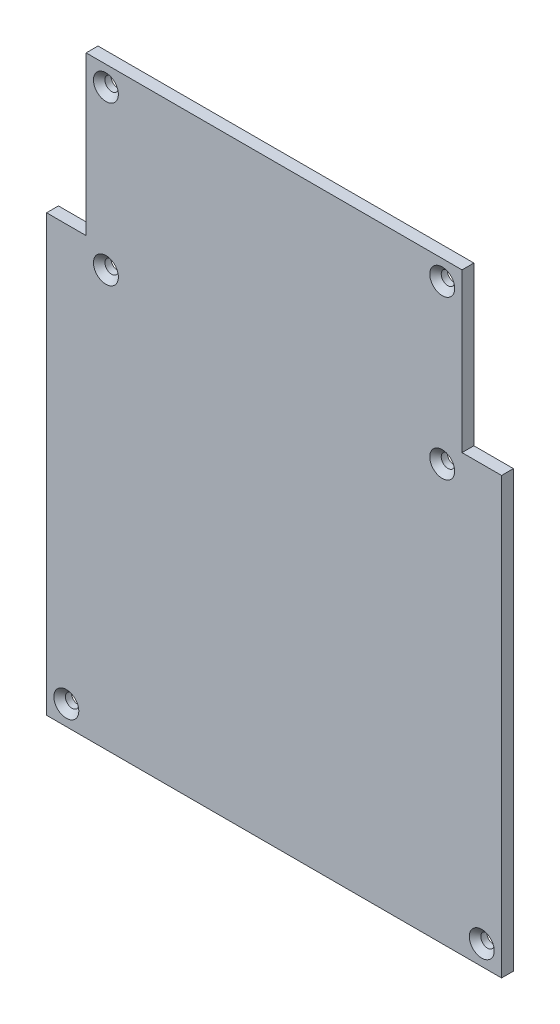
SolidWorks part; units mm, degrees
ref_plane "前基準面" through (0, 0, 0) normal (0, 0, 1) x (1, 0, 0)
ref_plane "上基準面" through (0, 0, 0) normal (0, 1, 0) x (1, 0, 0)
ref_plane "右基準面" through (0, 0, 0) normal (1, 0, 0) x (0, 0, -1)
sketch "草圖1" plane through (0, 0, 0) normal (0, 0, 1) x (1, 0, 0)
  line L0 (0, 75) -> (0, 0) construction
  line L1 (-57.5, -55) -> (57.5, -55)
  line L2 (-57.5, -55) -> (-57.5, 55)
  line L3 (-57.5, 55) -> (-47.5, 55)
  line L4 (57.5, -55) -> (57.5, 55)
  line L5 (-57.5, -55) -> (57.5, 55) construction
  line L6 (-57.5, 55) -> (57.5, -55) construction
  line L7 (-47.5, 95) -> (47.5, 95)
  line L8 (-47.5, 95) -> (-47.5, 55)
  line L10 (47.5, 95) -> (47.5, 55)
  line L11 (-47.5, 95) -> (47.5, 55) construction
  line L12 (-47.5, 55) -> (47.5, 95) construction
  line L13 (47.5, 55) -> (57.5, 55)
  point P0 (0, 0)
  point P6 (0, 75)
  dimension "D1" = 115
  dimension "D2" = 150
  dimension "D3" = 40
  dimension "D4" = 95
extrude "填料-伸長1" add sketch "草圖1" along normal blind 3
hole_wizard "M3 錐坑平頭螺釘的錐孔1" positions "草圖2" profile "草圖3" countersink size "M3" standard "ISO"
sketch "草圖2" plane through (0, 0, 3) normal (0, 0, 1) x (1, 0, 0)
  line L0 (-57.5, 55) -> (-57.5, -55) construction
  line L1 (57.5, -55) -> (57.5, 55) construction
  line L2 (-57.5, -55) -> (57.5, -55) construction
  line L3 (47.5, 95) -> (-47.5, 95) construction
  line L4 (-47.5, 95) -> (-47.5, 55) construction
  line L5 (47.5, 55) -> (47.5, 95) construction
  line L6 (57.5, 55) -> (47.5, 55) construction
  point P0 (-52.5, -50)
  point P2 (-42.5, 90)
  point P4 (-42.5, 50)
  point P6 (42.5, 90)
  point P8 (42.5, 50)
  point P10 (52.5, -50)
  dimension "D1" = 5
  dimension "D2" = 5
  dimension "D3" = 5
  dimension "D4" = 5
  dimension "D5" = 5
  dimension "D6" = 5
  dimension "D7" = 15
  dimension "D8" = 15
  dimension "D9" = 5
sketch "草圖3" plane through (-52.5, -50, 3) normal (1, 0, 0) x (0, -1, 0)
  line L0 (0, 0) -> (0, 16.0215)
  line L1 (0, 16.0215) -> (1.7, 15)
  line L2 (1.7, 15) -> (1.7, 1.45)
  line L3 (1.7, 1.45) -> (3.15, 0)
  line L5 (3.15, 0) -> (0, 0)
  line L6 (-1.7, 1.45) -> (-3.15, 0) construction
  line L10 (0, 16.0215) -> (-1.7, 15) construction
  line L11 (0, -6.35) -> (0, 107.95) construction
  dimension "鑽孔直徑" = 3.4
  dimension "鑽孔深度" = 15
  dimension "近端錐孔直徑" = 6.3
  dimension "近端錐孔角度" = 90
  dimension "導頭角度" = 118
